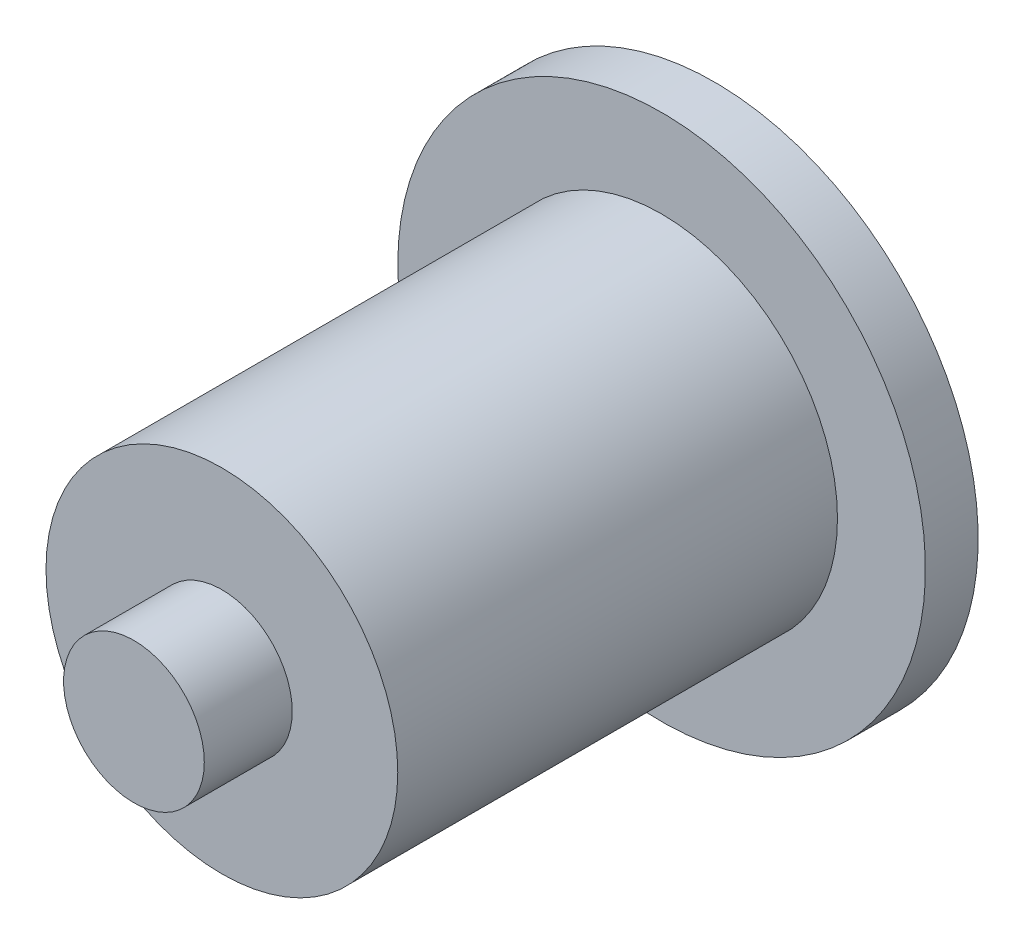
SolidWorks part; units mm, degrees
ref_plane "Front Plane" through (0, 0, 0) normal (0, 0, 1) x (1, 0, 0)
ref_plane "Top Plane" through (0, 0, 0) normal (0, 1, 0) x (1, 0, 0)
ref_plane "Right Plane" through (0, 0, 0) normal (1, 0, 0) x (0, 0, -1)
sketch "Sketch1" plane through (0, 0, 0) normal (0, 0, 1) x (1, 0, 0)
  circle A0 centre (0, 0) radius 10
  dimension "D1" = 20
extrude "Boss-Extrude1" add sketch "Sketch1" along normal blind 25
sketch "Sketch2" plane through (0, 0, 25) normal (0, 0, 1) x (1, 0, 0)
  circle A0 centre (0, 0) radius 4
  dimension "D1" = 8
extrude "Boss-Extrude2" add sketch "Sketch2" along normal blind 5
sketch "Sketch3" plane through (0, 0, 0) normal (0, 0, -1) x (-1, 0, 0)
  circle A0 centre (0, 0) radius 15
  dimension "D1" = 30
extrude "Boss-Extrude3" add sketch "Sketch3" along normal blind 3
